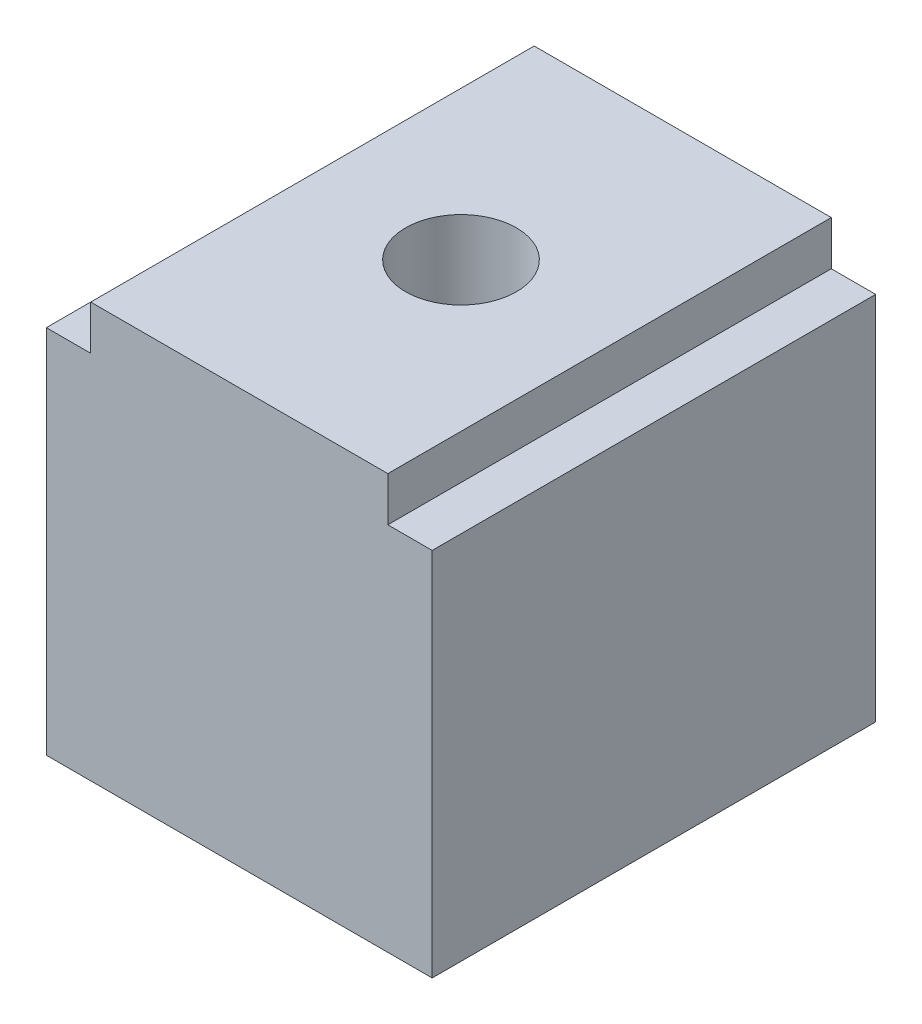
SolidWorks part; units mm, degrees
material "AISI 304"
ref_plane "Front Plane" through (0, 0, 0) normal (0, 0, 1) x (1, 0, 0)
ref_plane "Top Plane" through (0, 0, 0) normal (0, 1, 0) x (1, 0, 0)
ref_plane "Right Plane" through (0, 0, 0) normal (1, 0, 0) x (0, 0, -1)
sketch "Sketch1" plane through (0, 0, 0) normal (0, 1, 0) x (1, 0, 0)
  line L1 (-11.049, -12.7) -> (11.049, -12.7)
  line L2 (-11.049, -12.7) -> (-11.049, 12.7)
  line L3 (-11.049, 12.7) -> (11.049, 12.7)
  line L4 (11.049, -12.7) -> (11.049, 12.7)
  line L5 (-11.049, -12.7) -> (11.049, 12.7) construction
  line L6 (-11.049, 12.7) -> (11.049, -12.7) construction
  circle A0 centre (0, 0) radius 3.175
  point P0 (0, 0)
  dimension "D3" = 6.35
  dimension "D1" = 25.4
  dimension "D2" = 22.098
extrude "Boss-Extrude1" add sketch "Sketch1" along normal blind 23.749
sketch "Sketch3" plane through (0, 23.749, 0) normal (0, 1, 0) x (1, 0, 0)
  line L0 (-11.049, -12.7) -> (11.049, -12.7) construction
  line L1 (11.049, 12.7) -> (8.509, 12.7)
  line L2 (11.049, 12.7) -> (11.049, -12.7)
  line L3 (11.049, -12.7) -> (8.509, -12.7)
  line L4 (8.509, 12.7) -> (8.509, -12.7)
  line L5 (0, 12.7) -> (0, -12.7) construction
  line L6 (-8.509, 12.7) -> (-8.509, -12.7)
  line L7 (-11.049, -12.7) -> (-8.509, -12.7)
  line L8 (-11.049, 12.7) -> (-11.049, -12.7)
  line L9 (-11.049, 12.7) -> (-8.509, 12.7)
  dimension "D1" = 2.54
extrude "Cut-Extrude2" cut sketch "Sketch3" against normal blind 2.54
